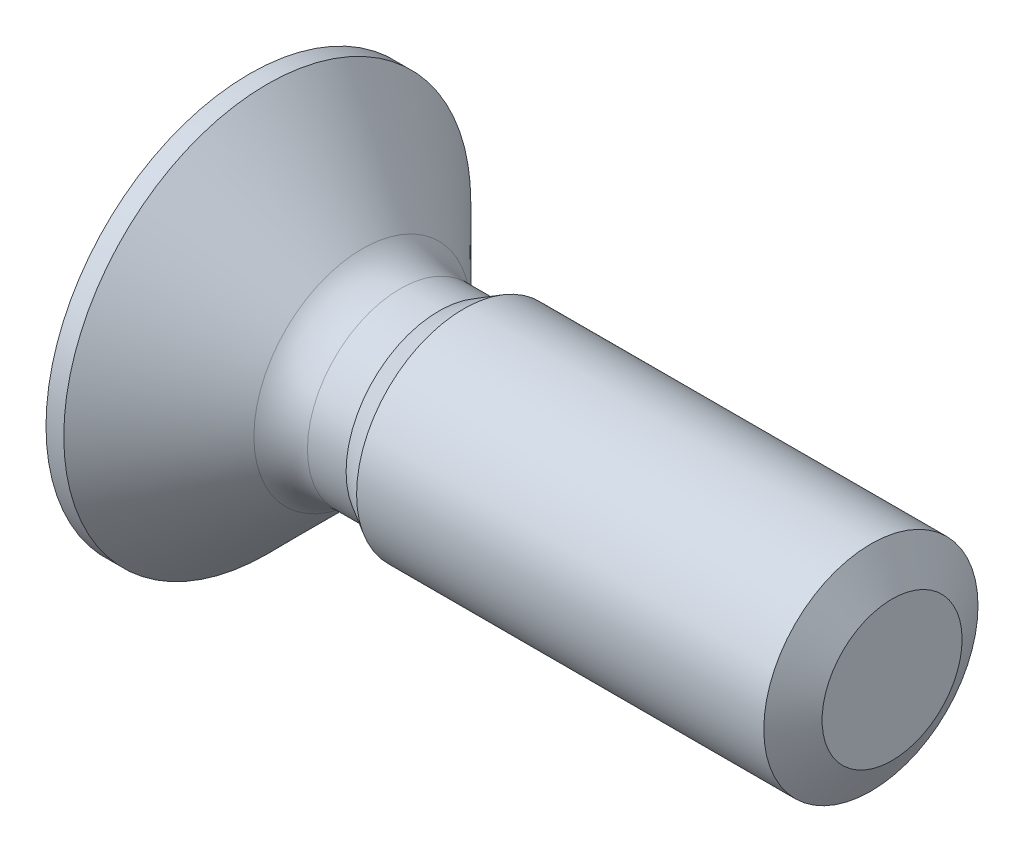
SolidWorks part; units mm, degrees
revolve "基体-旋转" add sketch "草图1" angle 360 about L0
sketch "草图1" plane through (0, 0, 0) normal (0, 0, 1) x (1, 0, 0)
  line L0 (0, 0) -> (4.4175, 0) construction
  line L1 (0, 0) -> (0, 1.9)
  line L2 (0, 1.9) -> (0.166, 1.9)
  line L3 (0.166, 1.9) -> (1.0536, 1.0124)
  line L4 (1.4071, 0.866) -> (1.7679, 0.866)
  line L5 (1.7679, 0.866) -> (2, 1)
  line L6 (2, 1) -> (6, 1)
  line L7 (6, 1) -> (6, 0)
  line L8 (0, 0) -> (6, 0)
  arc A0 (1.4071, 0.866) -> (1.0536, 1.0124) centre (1.4071, 1.366) cw
  point P12 (1.2, 0.866)
  dimension "D2" = 0.5
  dimension "D1" = 1.732
  dimension "d" = 2
  dimension "dk" = 3.8
  dimension "k" = 1.2
  dimension "D5" = 45
  dimension "a" = 0.8
  dimension "l" = 6
  dimension "D8" = 30
cosmetic thread "装饰螺纹线2" parameters "D1"=4, "D2"=1.6
ref_plane "前视" through (0, 0, 0) normal (0, 0, 1) x (1, 0, 0)
ref_plane "上视" through (0, 0, 0) normal (0, 1, 0) x (1, 0, 0)
ref_plane "右视" through (0, 0, 0) normal (1, 0, 0) x (0, 0, -1)
sketch "尺寸草图" plane through (0, 0, 0) normal (0, 0, 1) x (1, 0, 0)
  line L0 (0, 0) -> (6, 0)
  point P3 (1.2, 0)
  point P4 (0.8, 0)
  point P5 (2, 0)
  point P6 (3.8, 0)
  point P7 (4.1, 0)
  point P8 (3.5943, 0)
  point P9 (5.5, 0)
  point P10 (4.8, 0)
  point P11 (5.6, 0)
  dimension "d" = 2
  dimension "dk" = 3.8
  dimension "k" = 1.2
  dimension "a" = 0.8
  dimension "l" = 6
  dimension "r" = 0.5
  dimension "m" = 1.9
  dimension "h" = 1.2
  dimension "p" = 0.4
sketch "草图2" plane through (0, 0, 0) normal (0, 0, 1) x (1, 0, 0)
  line L0 (5.8022, 1) -> (6.2022, 1)
  line L1 (6.2022, 1) -> (6, 0.6536)
  line L2 (6, 0.6536) -> (5.8022, 1)
  line L3 (6, -1) -> (6, 1) construction
  line L6 (0, 0) -> (-0.4315, 0) construction
  dimension "D2" = 0.3464
  dimension "D3" = 1
  dimension "D4" = 60
revolve "切除-旋转1" cut sketch "草图2" angle 360 about L6
pattern_linear "阵列(线性)1" [suppressed] count 10 spacing 0.4 along (1, 0, 0)
sketch "草图3" plane through (0, 0, 0) normal (-1, 0, 0) x (0, 0, 1)
  line L0 (0, 0) -> (1.6329, 0) construction
  line L1 (0, 0) -> (0, 0.8499) construction
  line L2 (-0.95, 0.2) -> (0.95, 0.2)
  line L3 (-0.95, 0.2) -> (-0.95, -0.2)
  line L4 (-0.95, -0.2) -> (0.95, -0.2)
  line L5 (0.95, 0.2) -> (0.95, -0.2)
  dimension "m" = 1.9
  dimension "D1" = 0.4
ref_plane "基准面1" through (1.2, 0, 0) normal (-1, 0, 0) x (0, 0, 1)
sketch "草图4" plane through (1.2, 0, 0) normal (-1, 0, 0) x (0, 0, 1)
  point P0 (0, 0)
loft "切除-放样1" cut profiles "草图3", "草图4"
pattern_circular "阵列(圆周)1" count 2 every 90 about axis through (0, 0, 0) along (1, 0, 0) of "切除-放样1"
equation "\"l@草图1\" = \"l@尺寸草图\""
equation "\"k@草图1\" = \"k@尺寸草图\""
equation "\"a@草图1\" = \"a@尺寸草图\""
equation "\"d@草图1\" = \"d@尺寸草图\""
equation "\"dk@草图1\" = \"dk@尺寸草图\""
equation "\"D2@草图1\" = \"r@尺寸草图\""
equation "\"m@草图3\" = \"m@尺寸草图\""
equation "\"h@基准面1\" = \"h@尺寸草图\""
equation "\"D3@阵列(线性)1\" = \"p@尺寸草图\""
equation "\"D3@草图2\" = \"d@草图1\" / 2"
equation "\"D1@装饰螺纹线2\" = \"l@草图1\" - \"k@草图1\" - \"a@草图1\""
equation "\"D2@装饰螺纹线2\" = \"d@尺寸草图\"- \"p@尺寸草图\""
equation "\"D1@阵列(线性)1\" = (  \"l@草图1\" - \"k@草图1\" - \"a@草图1\" )  / \"p@尺寸草图\""
equation "\"D1@草图3\" = \"p@尺寸草图\""
equation "\"D1@草图1\" = \"d@尺寸草图\"*0.866"
equation "\"D2@草图2\" = \"p@尺寸草图\"*0.866"
equation "\"D1@草图2\" = \"p@尺寸草图\""
